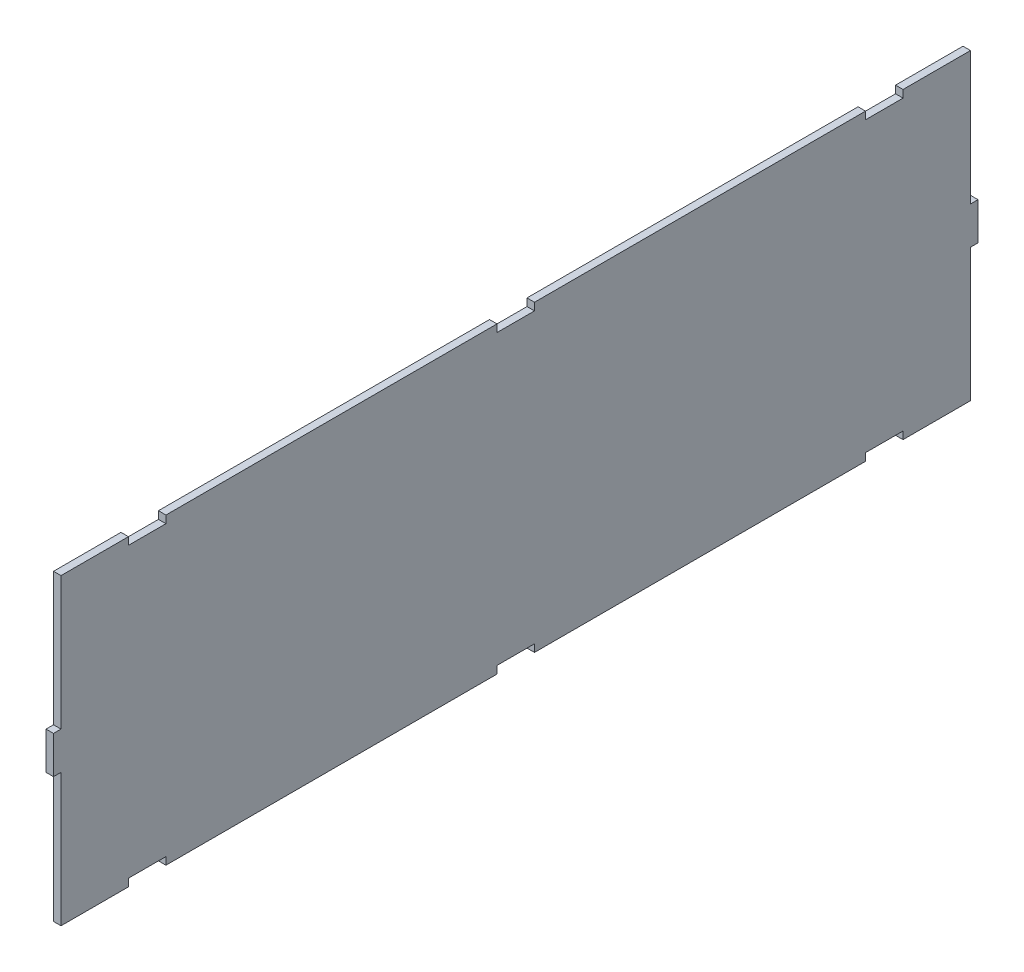
SolidWorks part; units mm, degrees
ref_plane "Front Plane" through (0, 0, 0) normal (0, 0, 1) x (1, 0, 0)
ref_plane "Top Plane" through (0, 0, 0) normal (0, 1, 0) x (1, 0, 0)
ref_plane "Right Plane" through (0, 0, 0) normal (1, 0, 0) x (0, 0, -1)
sketch "Sketch1" plane through (0, 0, 0) normal (1, 0, 0) x (0, 0, -1)
  line L0 (177.5, -3) -> (192.5, -3)
  line L1 (3, 0) -> (30, 0)
  line L3 (3, -121.38) -> (30, -121.38)
  line L5 (192.5, 0) -> (325, 0)
  line L6 (30, 0) -> (30, -3)
  line L7 (177.5, -3) -> (177.5, 0)
  line L8 (192.5, -3) -> (192.5, 0)
  line L9 (30, -3) -> (45, -3)
  line L10 (45, -3) -> (45, 0)
  line L11 (45, 0) -> (177.5, 0)
  line L12 (325, -3) -> (325, 0)
  line L13 (340, -3) -> (325, -3)
  line L14 (340, 0) -> (340, -3)
  line L15 (340, -121.38) -> (340, -118.38)
  line L16 (340, -118.38) -> (325, -118.38)
  line L17 (325, -118.38) -> (325, -121.38)
  line L18 (45, -118.38) -> (45, -121.38)
  line L19 (30, -118.38) -> (45, -118.38)
  line L20 (192.5, -118.38) -> (192.5, -121.38)
  line L21 (177.5, -118.38) -> (177.5, -121.38)
  line L22 (30, -121.38) -> (30, -118.38)
  line L23 (177.5, -118.38) -> (192.5, -118.38)
  line L24 (340, 0) -> (367, 0)
  line L25 (340, -121.38) -> (367, -121.38)
  line L26 (192.5, -121.38) -> (325, -121.38)
  line L27 (45, -121.38) -> (177.5, -121.38)
  line L31 (367, -53.19) -> (370, -53.19)
  line L32 (367, -68.19) -> (370, -68.19)
  line L35 (3, -68.19) -> (0, -68.19)
  line L36 (3, -53.19) -> (0, -53.19)
  line L39 (0, -53.19) -> (0, -68.19)
  line L40 (370, -53.19) -> (370, -68.19)
  line L41 (3, -53.19) -> (3, 0)
  line L42 (3, -68.19) -> (3, -121.38)
  line L43 (367, -53.19) -> (367, 0)
  line L44 (367, -68.19) -> (367, -121.38)
  dimension "D1" = 370
  dimension "D2" = 15
  dimension "D3" = 15
  dimension "D4" = 3
  dimension "D5" = 3
  dimension "D6" = 15
  dimension "D7" = 3
  dimension "D8" = 30
extrude "Boss-Extrude1" add sketch "Sketch1" along normal blind 3
